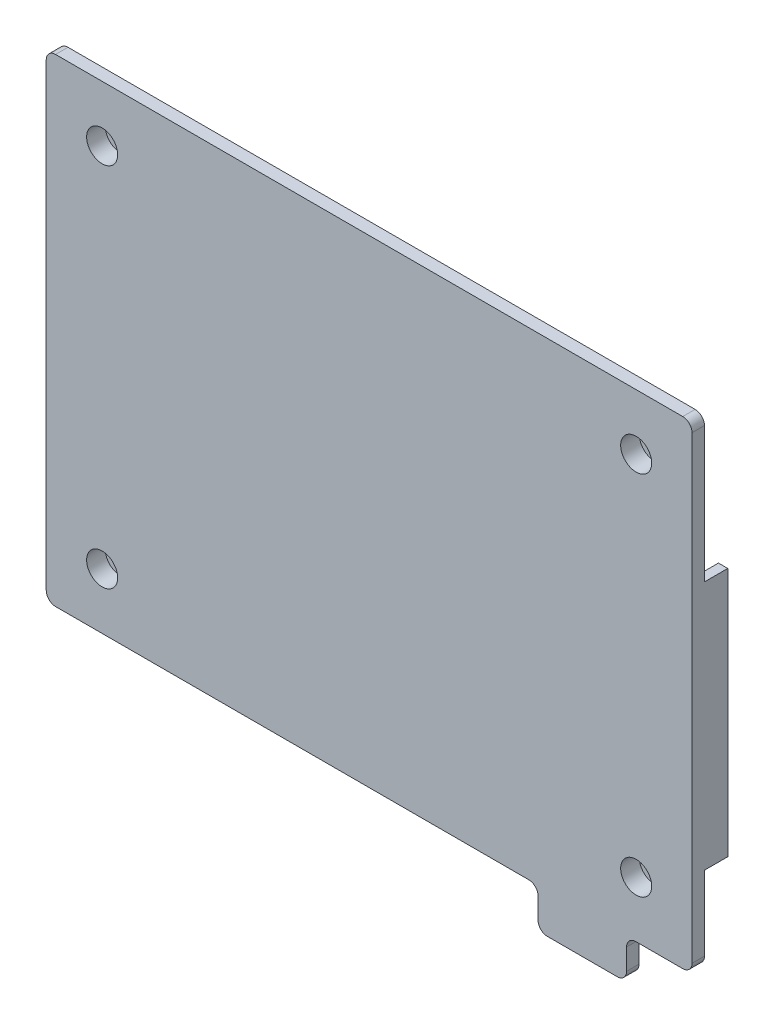
SolidWorks part; units mm, degrees
ref_plane "Front Plane" through (0, 0, 0) normal (0, 0, 1) x (1, 0, 0)
ref_plane "Top Plane" through (0, 0, 0) normal (0, 1, 0) x (1, 0, 0)
ref_plane "Right Plane" through (0, 0, 0) normal (1, 0, 0) x (0, 0, -1)
ref_plane "PCB-top" through (0, 0, 0) normal (0, 0, 1) x (1, 0, 0)
ref_plane "PCB-bottom" through (0, 0, -1.5875) normal (0, 0, 1) x (1, 0, 0)
sketch "Sketch1" plane through (0, 0, 8.9125) normal (0, 0, 1) x (1, 0, 0)
  line L0 (102, -2) -> (102, 75)
  line L1 (102, 75) -> (-2, 75)
  line L2 (-2, 75) -> (-2, -2)
  line L3 (-2, -2) -> (77.2, -2)
  line L4 (77.2, -2) -> (77.2, -8.4)
  line L5 (77.2, -8.4) -> (91.45, -8.4)
  line L6 (91.45, -8.4) -> (91.45, -2)
  line L7 (91.45, -2) -> (102, -2)
extrude "bottom-cover" add sketch "Sketch1" along normal blind 2
sketch "Sketch5" plane through (0, 0, 8.9125) normal (0, 0, -1) x (-1, 0, 0)
  line L0 (-102, -2) -> (-102, 75) construction
  line L1 (-102, 51.6941) -> (-100.5, 51.6941)
  line L2 (-102, 51.6941) -> (-102, 11.4799)
  line L3 (-102, 11.4799) -> (-100.5, 11.4799)
  line L4 (-100.5, 51.6941) -> (-100.5, 11.4799)
extrude "connector-panel" add sketch "Sketch5" along normal blind 3.75 contours L4 L3 L2 L1
sketch "Sketch6" plane through (0, 0, 8.9125) normal (0, 0, -1) x (-1, 0, 0)
  line L0 (-77.1937, 36.0578) -> (-77.6937, 36.0578) construction
  line L1 (-77.6937, 64.0578) -> (-13.6937, 64.0578)
  line L2 (-77.6937, 64.0578) -> (-77.6937, 8.0578)
  line L3 (-77.6937, 8.0578) -> (-13.6937, 8.0578)
  line L4 (-13.6937, 64.0578) -> (-13.6937, 8.0578)
  line L5 (-11.6937, 6.0578) -> (-79.6937, 6.0578)
  line L6 (-11.6937, 6.0578) -> (-11.6937, 66.0578)
  line L7 (-11.6937, 66.0578) -> (-79.6937, 66.0578)
  line L8 (-79.6937, 6.0578) -> (-79.6937, 66.0578)
  line L9 (-77.1937, 8.5578) -> (-77.1937, 63.5578) construction
  line L10 (-77.6937, 36.0578) -> (-79.6937, 36.0578) construction
  line L12 (-77.1937, 63.5578) -> (-14.1937, 63.5578) construction
  line L13 (-45.6937, 63.5578) -> (-45.6937, 64.0578) construction
  line L14 (-45.6937, 64.0578) -> (-45.6937, 66.0578) construction
  line L17 (-14.1937, 63.5578) -> (-14.1937, 8.5578) construction
  line L18 (-14.1937, 36.0578) -> (-13.6937, 36.0578) construction
  line L20 (-13.6937, 36.0578) -> (-11.6937, 36.0578) construction
  line L23 (-14.1937, 8.5578) -> (-77.1937, 8.5578) construction
  line L24 (-45.6937, 8.5578) -> (-45.6937, 8.0578) construction
  line L26 (-45.6937, 8.0578) -> (-45.6937, 6.0578) construction
extrude "battery-holder" add sketch "Sketch6" along normal blind 2
fillet "Fillet1" radius 1.5 8 edges at (102, -2, 9.9125) (102, 75, 9.9125) (-2, 75, 9.9125) (91.45, -8.4, 9.9125) (91.45, -2, 9.9125) (77.2, -2, 9.9125) (77.2, -8.4, 9.9125) (-2, -2, 9.9125)
ref_plane "Plane1" through (0, 0, 5) normal (0, 0, 1) x (1, 0, 0)
sketch "Sketch7" plane through (0, 0, 8.9125) normal (0, 0, -1) x (-1, 0, 0)
  circle A0 centre (-7, 66) radius 3.5
  circle A2 centre (-7, 7) radius 3.5
  circle A5 centre (-93, 7) radius 3.5
  circle A6 centre (-93, 66) radius 3.5
extrude "Boss-Extrude4" add sketch "Sketch7" along normal up to surface (3.9125 mm away) up to plane "Plane1"
sketch "Sketch8" plane through (0, 0, 5) normal (0, 0, -1) x (-1, 0, 0)
  circle A0 centre (-93, 66) radius 1.25
  circle A1 centre (-7, 66) radius 1.25
  circle A2 centre (-7, 7) radius 1.25
  circle A3 centre (-93, 7) radius 1.25
extrude "Cut-Extrude1" cut sketch "Sketch8" against normal blind 10
sketch "Sketch9" plane through (0, 0, 10.9125) normal (0, 0, 1) x (1, 0, 0)
  circle A0 centre (7, 66) radius 2.5
  circle A1 centre (93, 66) radius 2.5
  circle A2 centre (93, 7) radius 2.5
  circle A3 centre (7, 7) radius 2.5
extrude "Cut-Extrude2" cut sketch "Sketch9" against normal blind 3
